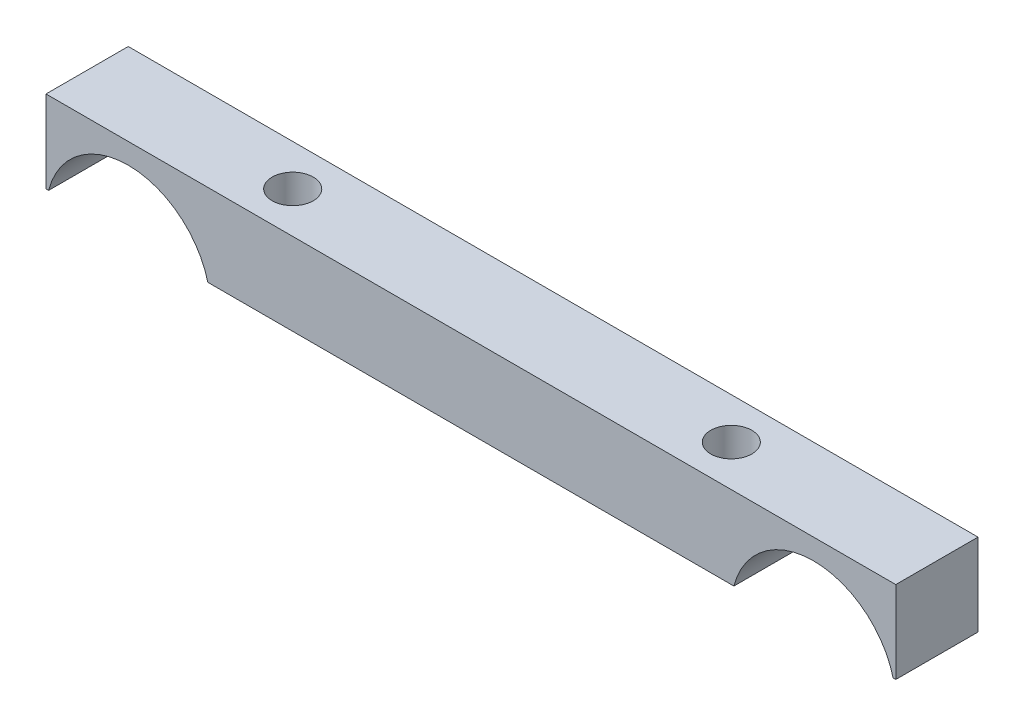
SolidWorks part; units mm, degrees
material "Delrin 2700 NC010, copolymère d'acétal à faible viscosité (SS)"
ref_plane "Plan de face" through (0, 0, 0) normal (0, 0, 1) x (1, 0, 0)
ref_plane "Plan de dessus" through (0, 0, 0) normal (0, 1, 0) x (1, 0, 0)
ref_plane "Plan de droite" through (0, 0, 0) normal (1, 0, 0) x (0, 0, -1)
sketch "Esquisse1" plane through (0, 0, 0) normal (0, 0, 1) x (1, 0, 0)
  line L0 (-31, 1.5) -> (-31, 7.5)
  line L1 (-31, 7.5) -> (31, 7.5)
  line L2 (31, 7.5) -> (31, 1.5)
  line L3 (31, 1.5) -> (30.8095, 1.5)
  line L4 (-30.8095, 1.5) -> (-31, 1.5)
  line L5 (-19.1905, 1.5) -> (19.1905, 1.5)
  arc A0 (-19.1905, 1.5) -> (-30.8095, 1.5) centre (-25, 0) ccw
  arc A1 (19.1905, 1.5) -> (30.8095, 1.5) centre (25, 0) cw
  dimension "D1" = 0
  dimension "D3" = 6
  dimension "D4" = 6
  dimension "D2" = 0
  dimension "D5" = 6
  dimension "D6" = 62
  dimension "D7" = 31
  dimension "D8" = 1.5
extrude "Boss.-Extru.1" add sketch "Esquisse1" along normal blind 6
sketch "Esquisse2" plane through (0, 7.5, 0) normal (0, 1, 0) x (1, 0, 0)
  circle A0 centre (-16, -3) radius 1.5
  circle A1 centre (16, -3) radius 1.5
  dimension "D1" = 3
  dimension "D2" = 3
extrude "Enlèv. mat.-Extru.1" cut sketch "Esquisse2" against normal blind 6
